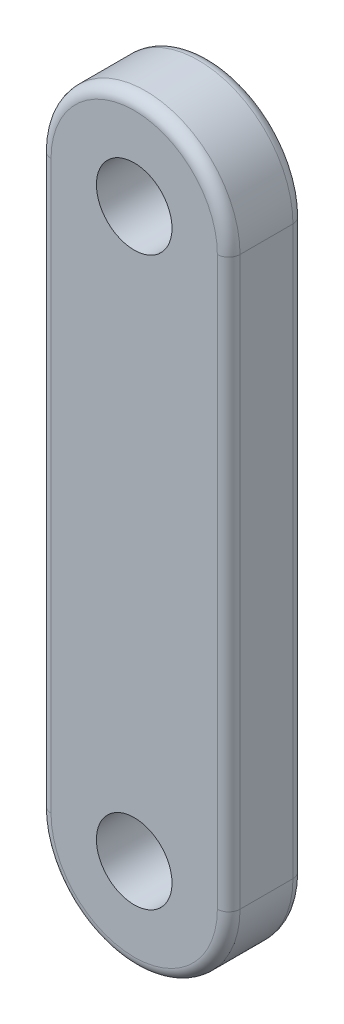
SolidWorks part; units mm, degrees
ref_plane "前视基准面" through (0, 0, 0) normal (0, 0, 1) x (1, 0, 0)
ref_plane "上视基准面" through (0, 0, 0) normal (0, 1, 0) x (1, 0, 0)
ref_plane "右视基准面" through (0, 0, 0) normal (1, 0, 0) x (0, 0, -1)
sketch "草图1" plane through (0, 0, 0) normal (0, 0, 1) x (1, 0, 0)
  line L0 (-20, 1.0294) -> (-20, 16.0294) construction
  line L1 (-22.5, 1.0294) -> (-22.5, 16.0294)
  line L2 (-17.5, 1.0294) -> (-17.5, 16.0294)
  arc A0 (-22.5, 1.0294) -> (-17.5, 1.0294) centre (-20, 1.0294) ccw
  arc A1 (-17.5, 16.0294) -> (-22.5, 16.0294) centre (-20, 16.0294) ccw
  circle A2 centre (-20, 16.0294) radius 1
  circle A3 centre (-20, 1.0294) radius 1
  point P2 (-20, 8.5294)
  dimension "D1" = 5
  dimension "D2" = 15
extrude "凸台-拉伸2" add sketch "草图1" along normal blind 2
fillet "圆角1" radius 0.3 8 edges at (-20, -1.4706, 2) (-22.5, 8.5294, 2) (-20, 18.5294, 2) (-20, -1.4706, 0) (-22.5, 8.5294, 0) (-20, 18.5294, 0) (-17.5, 8.5294, 2) (-17.5, 8.5294, 0)
